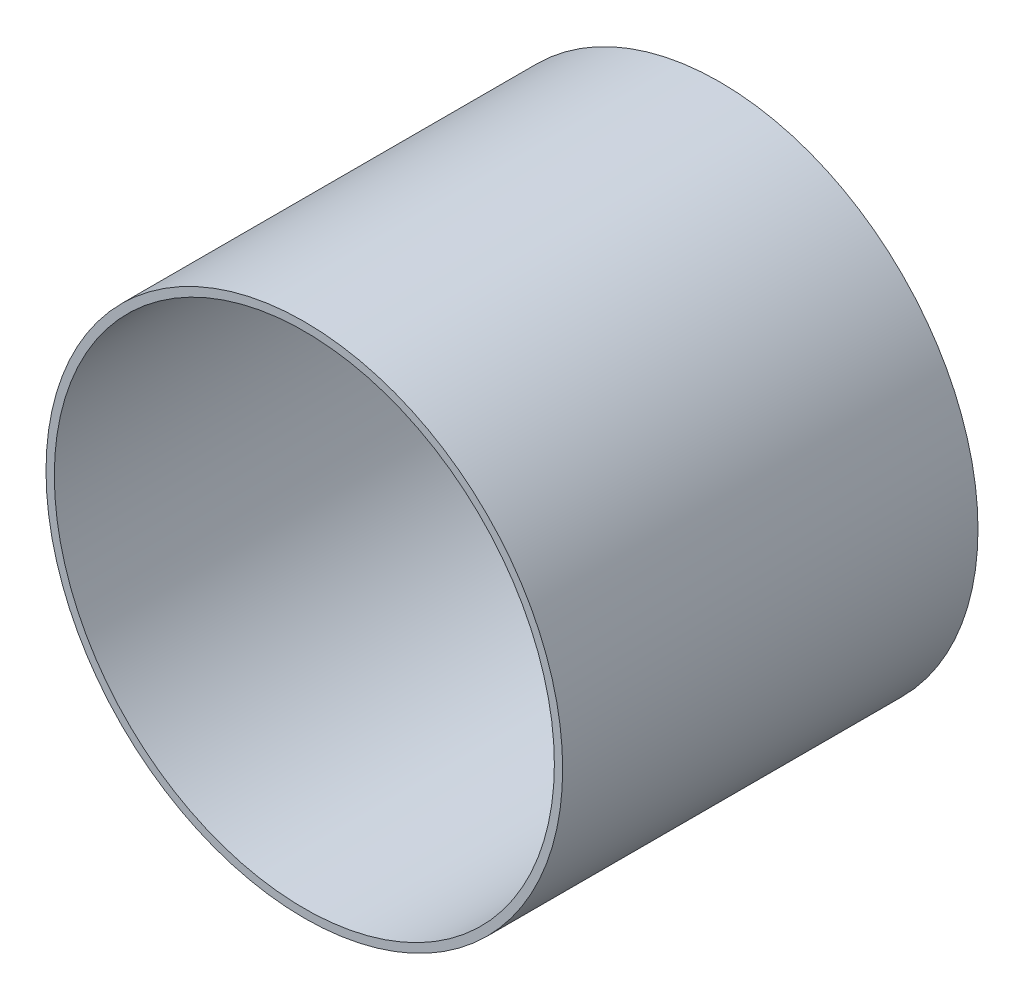
SolidWorks part; units mm, degrees
material "Латунь"
ref_plane "Спереди" through (0, 0, 0) normal (0, 0, 1) x (1, 0, 0)
ref_plane "Сверху" through (0, 0, 0) normal (0, 1, 0) x (1, 0, 0)
ref_plane "Справа" through (0, 0, 0) normal (1, 0, 0) x (0, 0, -1)
other "Configuration Table"
sketch "Эскиз1" plane through (0, 0, 0) normal (0, 0, 1) x (1, 0, 0)
  circle A0 centre (0, 0) radius 30.1
  circle A1 centre (0, 0) radius 31.1
  dimension "D1" = 60.2
  dimension "D2" = 1
extrude "Бобышка-Вытянуть1" add sketch "Эскиз1" along normal blind 50
